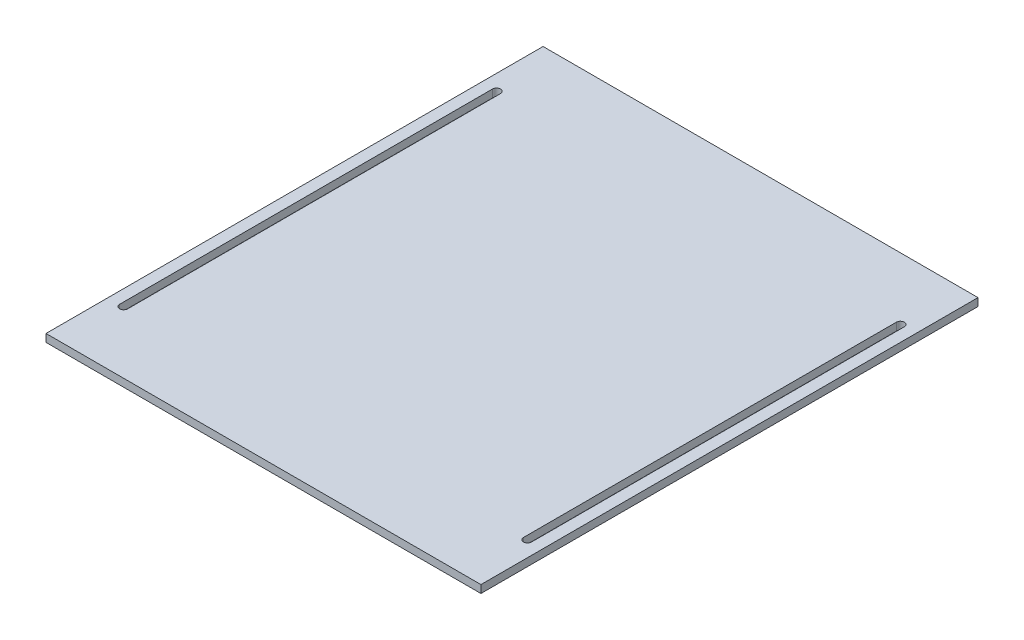
SolidWorks part; units mm, degrees
ref_plane "Front" through (0, 0, 0) normal (0, 0, 1) x (1, 0, 0)
ref_plane "Top" through (0, 0, 0) normal (0, 1, 0) x (1, 0, 0)
ref_plane "Right" through (0, 0, 0) normal (1, 0, 0) x (0, 0, -1)
sketch "Sketch1" plane through (0, 0, 0) normal (0, 1, 0) x (1, 0, 0)
  line L1 (-177.8, -203.2) -> (177.8, -203.2)
  line L2 (-177.8, -203.2) -> (-177.8, 203.2)
  line L3 (-177.8, 203.2) -> (177.8, 203.2)
  line L4 (177.8, -203.2) -> (177.8, 203.2)
  line L5 (-177.8, -203.2) -> (177.8, 203.2) construction
  line L6 (-177.8, 203.2) -> (177.8, -203.2) construction
  point P0 (0, 0)
  dimension "D1" = 355.6
  dimension "D2" = 406.4
extrude "Boss-Extrude1" add sketch "Sketch1" along normal blind 6.35 contours L3 L4 L1 L2
sketch "Sketch2" plane through (0, 6.35, 0) normal (0, 1, 0) x (1, 0, 0)
  line L0 (-165.1, 152.4) -> (-165.1, -152.4) construction
  line L1 (-161.8361, 152.4) -> (-161.8361, -152.4)
  line L2 (-168.3639, 152.4) -> (-168.3639, -152.4)
  line L5 (-50, 0) -> (50, 0) construction
  line L6 (0, -50) -> (0, 50) construction
  arc A0 (-161.8361, 152.4) -> (-168.3639, 152.4) centre (-165.1, 152.4) ccw
  arc A1 (-168.3639, -152.4) -> (-161.8361, -152.4) centre (-165.1, -152.4) ccw
  point P2 (-165.1, 0)
  point P9 (0, 0)
  dimension "D1" = 304.8
  dimension "D2" = 6.5278
  dimension "D3" = 165.1
extrude "Cut-Extrude1" cut sketch "Sketch2" against normal blind 6.35
mirror "Mirror1" about plane through (0, 0, 0) normal (1, 0, 0) of "Cut-Extrude1"
